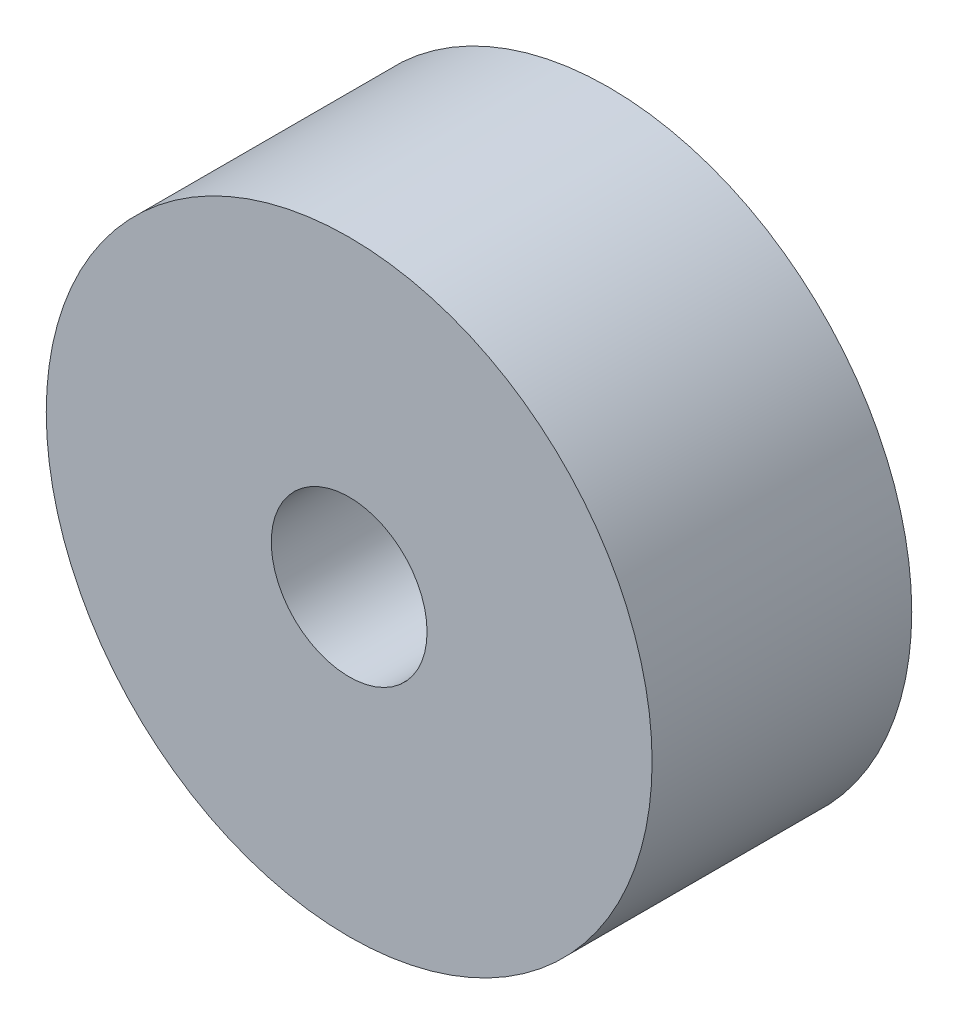
SolidWorks part; units mm, degrees
material "Rubber"
ref_plane "Front Plane" through (0, 0, 0) normal (0, 0, 1) x (1, 0, 0)
ref_plane "Top Plane" through (0, 0, 0) normal (0, 1, 0) x (1, 0, 0)
ref_plane "Right Plane" through (0, 0, 0) normal (1, 0, 0) x (0, 0, -1)
sketch "Sketch1" plane through (0, 0, 0) normal (0, 0, 1) x (1, 0, 0)
  circle A0 centre (0, 0) radius 350
  circle A1 centre (0, 0) radius 90
  dimension "D1" = 700
  dimension "D2" = 180
extrude "Boss-Extrude1" add sketch "Sketch1" along normal blind 300
